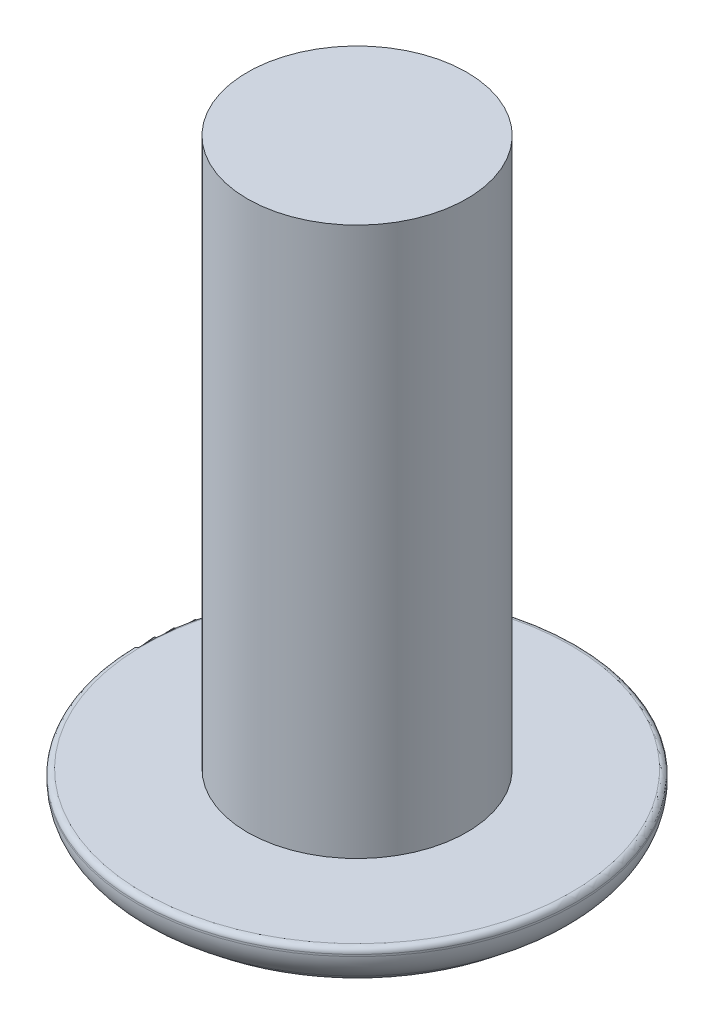
SolidWorks part; units mm, degrees
material "6061-T6 (SS)"
ref_plane "Front Plane" through (0, 0, 0) normal (1, 0, 0) x (0, 1, 0)
ref_plane "Top Plane" through (0, 0, 0) normal (0, 0, 1) x (0, 1, 0)
ref_plane "Right Plane" through (0, 0, 0) normal (0, 1, 0) x (-1, 0, 0)
sketch "Sketch2" plane through (0, 0, 0) normal (1, 0, 0) x (0, 1, 0)
  line L0 (-34.6211, 0) -> (64.2077, 0) construction
  line L1 (0, 24.0541) -> (0, -29.2793) construction
  line L2 (0, 0) -> (0, 10)
  line L3 (0, 10) -> (50, 10)
  line L4 (50, 10) -> (50, 0)
  line L5 (50, 0) -> (0, 0)
  line L6 (0, 10) -> (0, 20)
  line L7 (0, 20) -> (-2, 20)
  line L8 (-2, 20) -> (-2, 0)
  line L9 (-2, 0) -> (0, 0)
  line L10 (-10, 0) -> (0, 0)
  arc A0 (-2, 20) -> (-10, 0) centre (19, 0) ccw
  dimension "D5" = 29
  dimension "D1" = 20
  dimension "D2" = 50
  dimension "D3" = 40
  dimension "D4" = 2
  dimension "D6" = 10
revolve "Revolve1" add sketch "Sketch2" angle 360 about L0
fillet "Fillet1" radius 3 1 edges at (0, -2, -20)
fillet "Fillet2" radius 0.5 1 edges at (0, 0, -20)
